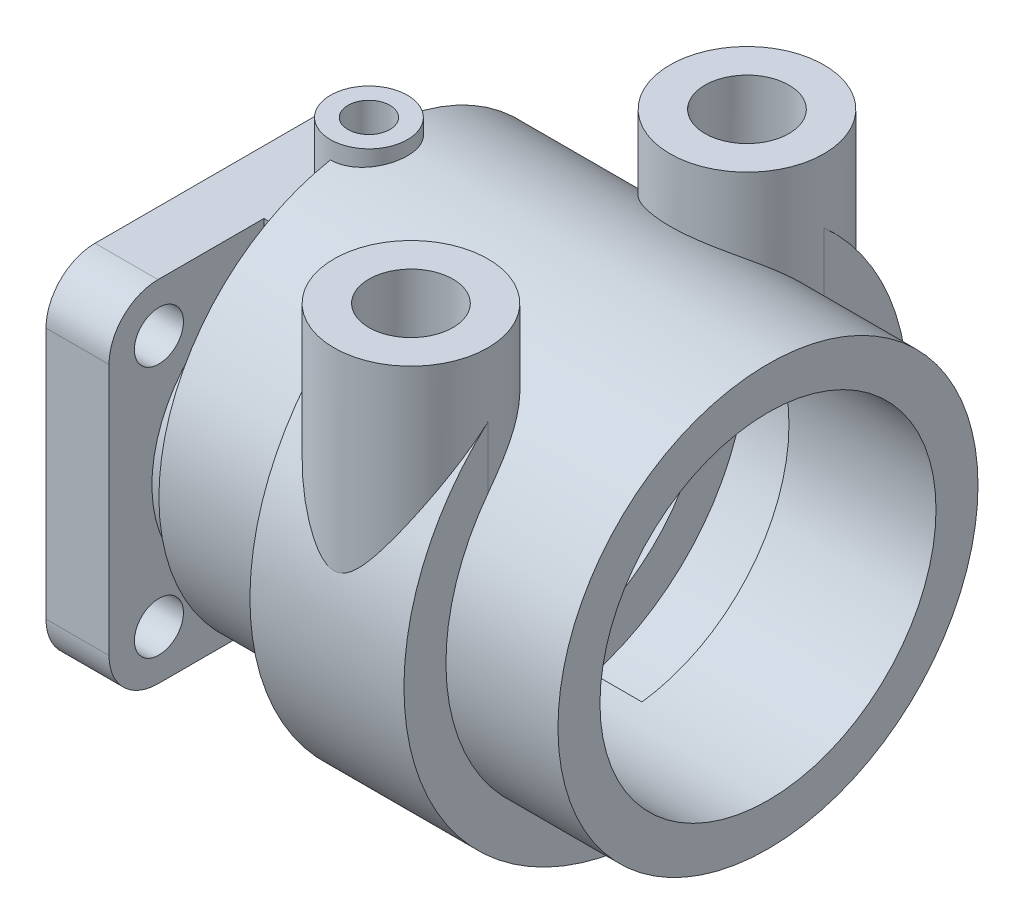
SolidWorks part; units mm, degrees
ref_plane "前视基准面" through (0, 0, 0) normal (0, 0, 1) x (1, 0, 0)
ref_plane "上视基准面" through (0, 0, 0) normal (0, 1, 0) x (1, 0, 0)
ref_plane "右视基准面" through (0, 0, 0) normal (1, 0, 0) x (0, 0, -1)
sketch "草图1" plane through (0, 0, 0) normal (1, 0, 0) x (0, 0, -1)
  line L1 (18.13, 25) -> (-18.13, 25)
  line L2 (25.13, 18) -> (25.13, -18)
  line L3 (18.13, -25) -> (-18.13, -25)
  line L4 (-25.13, 18) -> (-25.13, -18)
  line L5 (0, -25) -> (0, 25) construction
  line L6 (25.13, 0) -> (-25.13, 0) construction
  arc A0 (18.13, 25) -> (25.13, 18) centre (18.13, 18) cw
  arc A1 (25.13, -18) -> (18.13, -25) centre (18.13, -18) cw
  arc A2 (-18.13, -25) -> (-25.13, -18) centre (-18.13, -18) cw
  arc A3 (-18.13, 25) -> (-25.13, 18) centre (-18.13, 18) ccw
  circle A4 centre (-18, 18) radius 3.5
  circle A5 centre (-18, -18) radius 3.5
  circle A6 centre (18, -18) radius 3.5
  circle A7 centre (18, 18) radius 3.5
  point P0 (0, 0)
  dimension "D1" = 7
extrude "凸台-拉伸1" add sketch "草图1" along normal blind 9
sketch "草图2" plane through (0, 0, 0) normal (-1, 0, 0) x (0, 0, 1)
  circle A0 centre (0, 0) radius 19
extrude "切除-拉伸1" cut sketch "草图2" against normal blind 5
sketch "草图3" plane through (9, 0, 0) normal (1, 0, 0) x (0, 0, -1)
  circle A0 centre (0, 0) radius 19
extrude "凸台-拉伸2" add sketch "草图3" along normal blind 12
sketch "草图4" plane through (5, 0, 0) normal (-1, 0, 0) x (0, 0, 1)
  circle A0 centre (0, 0) radius 11
extrude "切除-拉伸2" cut sketch "草图4" against normal blind 22
sketch "草图6" plane through (21, 0, 0) normal (1, 0, 0) x (0, 0, -1)
  circle A0 centre (0, 10) radius 30
extrude "凸台-拉伸4" add sketch "草图6" along normal blind 57
sketch "草图9" plane through (78, 0, 0) normal (1, 0, 0) x (0, 0, -1)
  circle A0 centre (0, 10) radius 24
extrude "切除-拉伸3" cut sketch "草图9" against normal blind 51
sketch "草图10" plane through (5, 0, 0) normal (-1, 0, 0) x (0, 0, 1)
  circle A0 centre (0, 0) radius 11
extrude "切除-拉伸4" cut sketch "草图10" against normal blind 22
sketch "草图11" plane through (0, 0, 0) normal (0, 1, 0) x (1, 0, 0)
  circle A0 centre (21, 0) radius 5.5
extrude "凸台-拉伸5" add sketch "草图11" along normal blind 42 and the other way blind 5
sketch "草图12" plane through (0, 42, 0) normal (0, 1, 0) x (1, 0, 0)
  circle A0 centre (21, 0) radius 3
extrude "切除-拉伸5" cut sketch "草图12" against normal blind 46
sketch "草图13" plane through (0, 0, 0) normal (0, 0, 1) x (1, 0, 0)
  line L1 (6.6498, 25) -> (16.4433, 25)
  line L2 (6.6498, 25) -> (6.6498, 15)
  line L3 (6.6498, 15) -> (16.4433, 15)
  line L4 (16.4433, 25) -> (16.4433, 15)
extrude "凸台-拉伸6" add sketch "草图13" along normal blind 3 and the other way blind 3
sketch "草图14" plane through (0, 0, 0) normal (0, 1, 0) x (1, 0, 0)
  circle A0 centre (51, 24) radius 11
extrude "凸台-拉伸7" add sketch "草图14" along normal blind 46
sketch "草图15" plane through (0, 0, 0) normal (0, 1, 0) x (1, 0, 0)
  circle A0 centre (51, -24) radius 11
extrude "凸台-拉伸8" add sketch "草图15" along normal blind 46
sketch "草图16" plane through (0, 46, 0) normal (0, 1, 0) x (1, 0, 0)
  circle A0 centre (51, 24) radius 5.5
extrude "切除-拉伸6" cut sketch "草图16" against normal blind 46
sketch "草图17" plane through (0, 0, 0) normal (0, 1, 0) x (1, 0, 0)
  circle A0 centre (51, -24) radius 5.5
extrude "切除-拉伸8" cut sketch "草图17" along normal blind 53
sketch "草图18" plane through (0, 0, 0) normal (0, -1, 0) x (-1, 0, 0)
  circle A0 centre (-51, 24) radius 11
extrude "切除-拉伸9" cut sketch "草图18" against normal blind 10
sketch "草图19" plane through (0, 0, 0) normal (0, -1, 0) x (1, 0, 0)
  circle A0 centre (51, 24) radius 11
extrude "切除-拉伸10" cut sketch "草图19" against normal blind 10
sketch "草图20" plane through (78, 0, 0) normal (1, 0, 0) x (0, 0, -1)
  line L2 (24, 22.0245) -> (24, 36.8328)
  line L3 (-24, 22.0245) -> (-24, 36.8328)
  arc A0 (-24, 36.8328) -> (-25, 35.9037) centre (0, 10) ccw
  arc A1 (24, 22.0245) -> (-24, 22.0245) centre (0, 10) ccw
  arc A2 (-25, 35.9037) -> (25, 35.9037) centre (0, 10) ccw
  arc A3 (25, 35.9037) -> (24, 36.8328) centre (0, 10) ccw
  point P7 (24, 10)
  point P10 (-25, 10)
extrude "凸台-拉伸9" add sketch "草图20" against normal blind 38
sketch "草图21" plane through (78, 0, 0) normal (1, 0, 0) x (0, 0, -1)
  circle A0 centre (2.048, 13.6649) radius 49.2552
extrude "切除-拉伸18" cut sketch "草图21" against normal blind 16
sketch "草图22" plane through (62, 0, 0) normal (1, 0, 0) x (0, 0, -1)
  circle A0 centre (0, 10) radius 30
extrude "凸台-拉伸10" add sketch "草图22" along normal blind 16
sketch "草图23" plane through (78, 0, 0) normal (1, 0, 0) x (0, 0, -1)
  circle A0 centre (0, 10) radius 24
extrude "切除-拉伸19" cut sketch "草图23" against normal blind 21
sketch "草图24" plane through (57, 0, 0) normal (1, 0, 0) x (0, 0, -1)
  line L0 (24, 10) -> (24, 28)
  line L1 (-24, 10) -> (-24, 28)
  line L2 (3, -13.8118) -> (3, -19.8496)
  line L4 (-3, -16.9187) -> (-3, -13.8118)
  line L5 (-3, -16.9187) -> (-3, -19.8496)
  arc A1 (-24, 28) -> (-3, -19.8496) centre (0, 10) ccw
  arc A2 (-3, -13.8118) -> (3, -13.8118) centre (0, 10) ccw
  arc A3 (3, -19.8496) -> (24, 28) centre (0, 10) ccw
  arc A4 (24, 10) -> (-24, 10) centre (0, 10) ccw
  point P2 (3, 0)
  point P3 (3, -14)
  point P5 (-3, 0)
  point P12 (-3, -16.9187)
extrude "切除-拉伸21" cut sketch "草图24" against normal blind 12
sketch "草图25" plane through (45, 0, 0) normal (1, 0, 0) x (0, 0, -1)
  circle A0 centre (0, 10) radius 24
extrude "切除-拉伸22" cut sketch "草图25" against normal blind 18.5
sketch "草图26" plane through (5, 0, 0) normal (-1, 0, 0) x (0, 0, 1)
  circle A0 centre (0, 0) radius 11
extrude "切除-拉伸23" cut sketch "草图26" against normal blind 31.5
sketch "草图27" plane through (0, 46, 0) normal (0, 1, 0) x (1, 0, 0)
  circle A0 centre (51, -24) radius 6
extrude "切除-拉伸24" cut sketch "草图27" against normal blind 36
sketch "草图28" plane through (0, 46, 0) normal (0, 1, 0) x (1, 0, 0)
  circle A0 centre (51, 24) radius 6
extrude "切除-拉伸25" cut sketch "草图28" against normal blind 36
